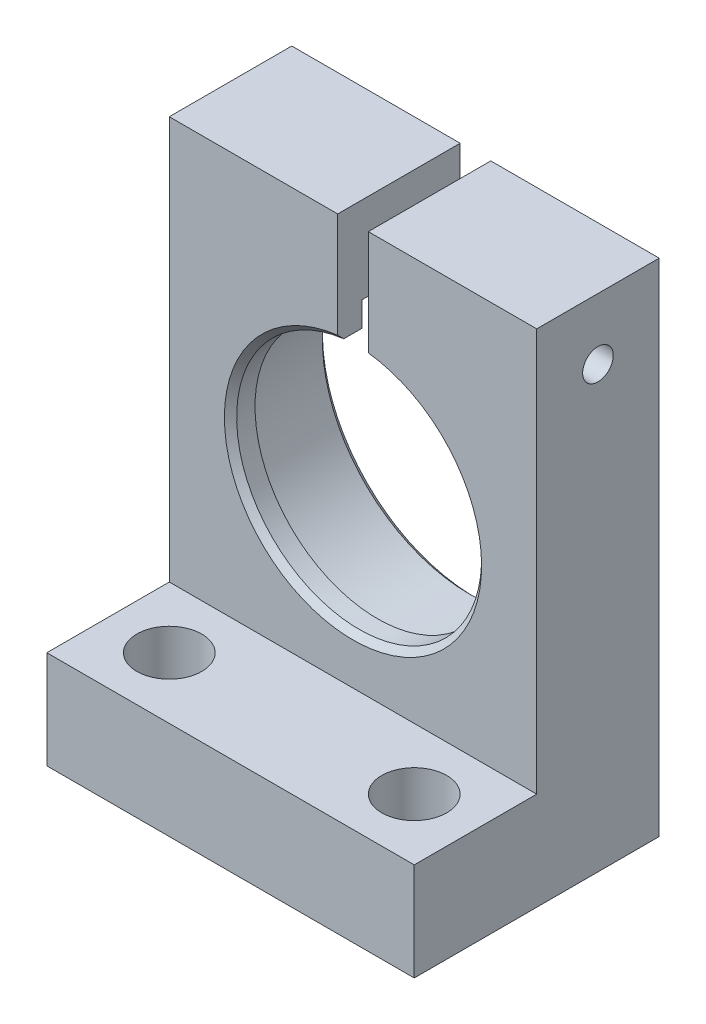
SolidWorks part; units mm, degrees
material "AISI 1045 Steel, cold drawn"
ref_plane "Front Plane" through (0, 0, 0) normal (0, 0, 1) x (1, 0, 0)
ref_plane "Top Plane" through (0, 0, 0) normal (0, 1, 0) x (1, 0, 0)
ref_plane "Right Plane" through (0, 0, 0) normal (1, 0, 0) x (0, 0, -1)
sketch "Sketch1" plane through (0, 0, 0) normal (0, 0, 1) x (1, 0, 0)
  line L1 (15, -21.9) -> (-15, -21.9)
  line L2 (15, -21.9) -> (15, 19)
  line L3 (15, 19) -> (-15, 19)
  line L4 (-15, -21.9) -> (-15, 19)
  line L5 (15, -21.9) -> (-15, 19) construction
  line L6 (15, 19) -> (-15, -21.9) construction
  circle A0 centre (0, 0) radius 12
  point P3 (0, -1.45)
  dimension "D1" = 24
  dimension "D2" = 19
  dimension "D3" = 21.9
  dimension "D4" = 30
extrude "Boss-Extrude1" add sketch "Sketch1" along normal blind 10
sketch "Sketch2" plane through (0, 0, 10) normal (0, 0, -1) x (-1, 0, 0)
  circle A0 centre (0, 0) radius 12 construction
  circle A1 centre (0, 0) radius 12
  circle A2 centre (0, 0) radius 10
  dimension "D1" = 20
extrude "Boss-Extrude2" add sketch "Sketch2" along normal blind 2
sketch "Sketch3" plane through (0, 0, 10) normal (0, 0, 1) x (1, 0, 0)
  line L0 (15, 19) -> (-15, 19) construction
  line L1 (1.25, 9.9216) -> (-1.25, 9.9216)
  line L2 (1.25, 9.9216) -> (1.25, 19)
  line L3 (1.25, 19) -> (-1.25, 19)
  line L4 (-1.25, 9.9216) -> (-1.25, 19)
  line L5 (1.25, 9.9216) -> (-1.25, 19) construction
  line L6 (1.25, 19) -> (-1.25, 9.9216) construction
  circle A0 centre (0, 0) radius 10 construction
  point P0 (0, 14.4608)
  dimension "D1" = 2.5
extrude "Cut-Extrude1" cut sketch "Sketch3" against normal through all
hole_wizard "CBORE for M3 SHCS1" positions "Sketch4" profile "Sketch5" counterbore size "M3" standard "ANSI Metric"
sketch "Sketch4" plane through (15, 0, 0) normal (1, 0, 0) x (0, 0, -1)
  line L0 (0, -21.9) -> (0, 19) construction
  line L1 (-10, 19) -> (0, 19) construction
  point P0 (-5, 14)
  dimension "D1" = 5
  dimension "D2" = 5
sketch "Sketch5" plane through (15, 14, 5) normal (0, 1, 0) x (0, 0, -1)
  line L0 (0, 0) -> (0, 13.75)
  line L1 (0, 13.75) -> (1.6, 13.75)
  line L3 (1.6, 13.75) -> (1.6, 3)
  line L4 (1.6, 3) -> (3.25, 3)
  line L5 (3.25, 3) -> (3.25, 0)
  line L7 (3.25, 0) -> (0, 0)
  line L11 (0, -6.35) -> (0, 107.95) construction
  dimension "Thru Hole Dia." = 3.2
  dimension "Thru Hole Depth" = 13.75
  dimension "C'Bore Dia." = 6.5
  dimension "C'Bore Depth" = 3
hole_wizard "Tap Drill for M3x0.5 Tap1" positions "Sketch6" profile "Sketch7" hole size "M3x0.5" standard "ANSI Metric" end condition up to next
sketch "Sketch6" plane through (-15, 0, 0) normal (-1, 0, 0) x (0, 0, 1)
  line L0 (10, 19) -> (10, -21.9) construction
  line L1 (10, 19) -> (0, 19) construction
  point P0 (5, 14)
  dimension "D1" = 5
  dimension "D2" = 5
sketch "Sketch7" plane through (-15, 14, 5) normal (0, 1, 0) x (0, 0, 1)
  line L0 (0, 0) -> (0, 13.75)
  line L1 (0, 13.75) -> (1.25, 13.75)
  line L2 (1.25, 13.75) -> (1.25, 0)
  line L5 (1.25, 0) -> (0, 0)
  line L11 (0, -6.35) -> (0, 107.95) construction
  dimension "Thru Hole Dia." = 2.5
  dimension "Thru Hole Depth" = 13.75
chamfer "Chamfer1" distance 0.5 angle 45 2 edges at (0, -10, 10) (0, -12, 0)
sketch "Sketch8" plane through (0, -21.9, 0) normal (0, -1, 0) x (1, 0, 0)
  line L1 (-15, 10) -> (15, 10)
  line L2 (-15, 10) -> (-15, 20)
  line L3 (-15, 20) -> (15, 20)
  line L4 (15, 10) -> (15, 20)
  dimension "D1" = 10
extrude "Boss-Extrude3" add sketch "Sketch8" against normal blind 8
hole_wizard "M5 Clearance Hole1" positions "Sketch9" profile "Sketch10" hole size "M5" standard "ANSI Metric" end condition up to next
sketch "Sketch9" plane through (0, -13.9, 0) normal (0, 1, 0) x (1, 0, 0)
  line L0 (15, -20) -> (-15, -20) construction
  line L1 (-15, -20) -> (-15, -10) construction
  line L2 (0, -10) -> (0, -20) construction
  line L4 (-10.5, -10) -> (10.5, -10) construction
  point P0 (-10, -15)
  point P14 (10, -15)
  point P16 (0, -10)
  point P17 (0, -10)
  dimension "D1" = 5
  dimension "D2" = 5
sketch "Sketch10" plane through (-10, -13.9, 15) normal (1, 0, 0) x (0, 0, 1)
  line L0 (0, 0) -> (0, 8)
  line L1 (0, 8) -> (2.65, 8)
  line L2 (2.65, 8) -> (2.65, 0)
  line L5 (2.65, 0) -> (0, 0)
  line L11 (0, -6.35) -> (0, 107.95) construction
  dimension "Thru Hole Dia." = 5.3
  dimension "Thru Hole Depth" = 8
mirror "Mirror1" about plane through (0, 0, 0) normal (1, 0, 0) of bodies 107
delete or keep bodies "Body-Delete/Keep 1" type delete bodies bodies 107
